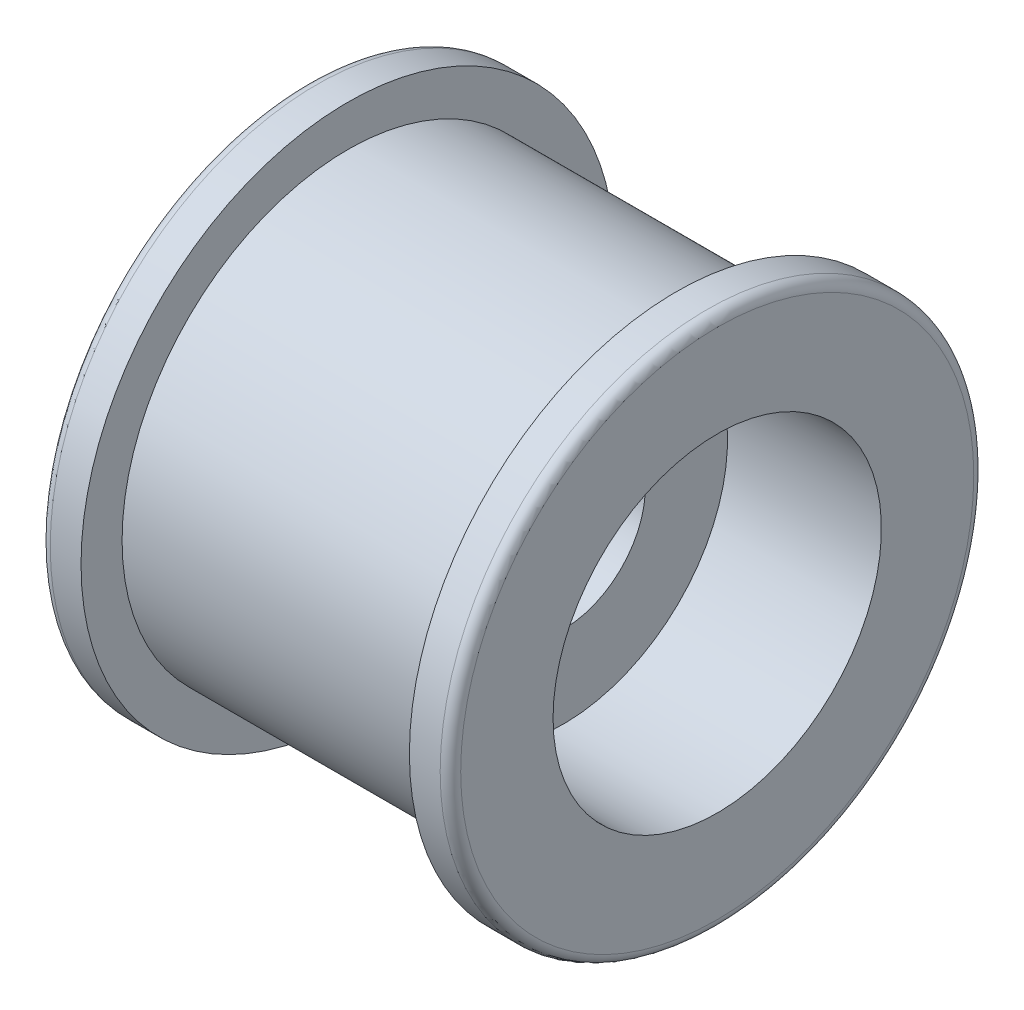
SolidWorks part; units mm, degrees
ref_plane "Front Plane" through (0, 0, 0) normal (0, 0, 1) x (1, 0, 0)
ref_plane "Top Plane" through (0, 0, 0) normal (0, 1, 0) x (1, 0, 0)
ref_plane "Right Plane" through (0, 0, 0) normal (1, 0, 0) x (0, 0, -1)
sketch "Sketch1" plane through (0, 0, 0) normal (0, 0, 1) x (1, 0, 0)
  line L3 (19.9696, 4) -> (19.9696, 7)
  line L4 (17.9696, 7) -> (1.9696, 7)
  line L5 (-0.0304, 7) -> (-0.0304, 4)
  line L6 (-15.2512, -4) -> (25.8916, -4) construction
  line L7 (19.9696, 4) -> (12.4696, 4)
  line L8 (7.4696, 4) -> (7.4696, 0)
  line L9 (7.4696, 0) -> (12.4696, 0)
  line L10 (12.4696, 0) -> (12.4696, 4)
  line L11 (7.4696, 4) -> (-0.0304, 4)
  line L14 (19.9696, 7) -> (19.9696, 9)
  line L15 (19.9696, 9) -> (17.9696, 9)
  line L16 (17.9696, 7) -> (17.9696, 9)
  line L18 (-0.0304, 7) -> (-0.0304, 9)
  line L19 (-0.0304, 9) -> (1.9696, 9)
  line L20 (1.9696, 7) -> (1.9696, 9)
  point P9 (9.9696, 0)
  point P12 (9.9696, 7)
  dimension "D1" = 7.5
  dimension "D2" = 8
  dimension "D3" = 2
  dimension "D4" = 20
  dimension "D5" = 3
  dimension "D6" = 2
revolve "Revolve1" add sketch "Sketch1" angle 360 about L6
fillet "Fillet2" radius 0.5 2 edges at (-0.0304, -4, 13) (19.9696, -4, 13)
